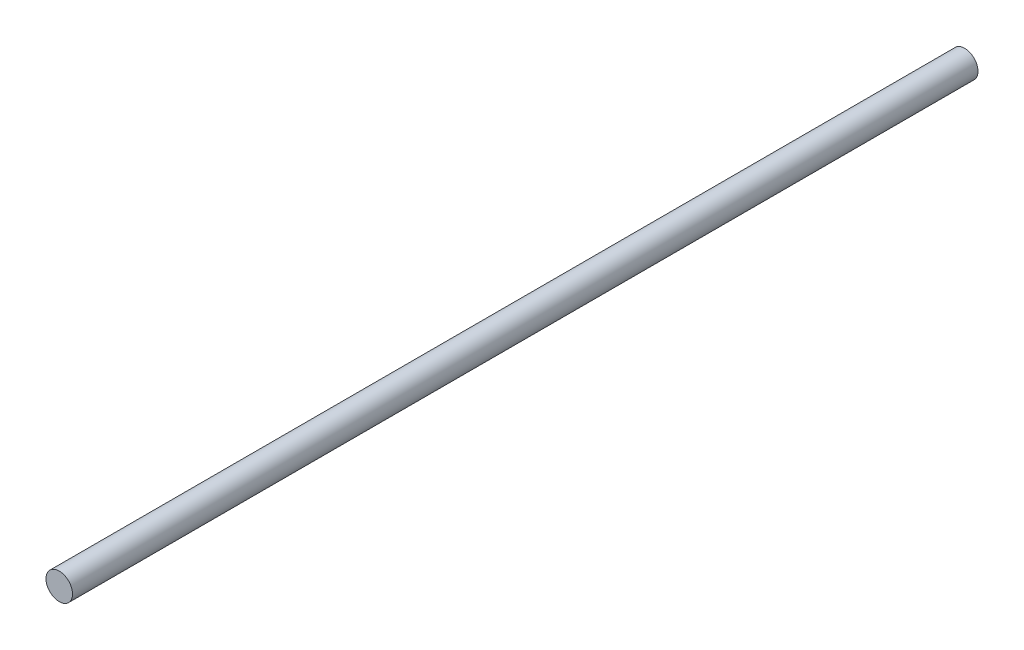
SolidWorks part; units mm, degrees
ref_plane "Płaszczyzna przednia" through (0, 0, 0) normal (0, 0, 1) x (1, 0, 0)
ref_plane "Płaszczyzna górna" through (0, 0, 0) normal (0, 1, 0) x (1, 0, 0)
ref_plane "Płaszczyzna prawa" through (0, 0, 0) normal (1, 0, 0) x (0, 0, -1)
sketch "Szkic1" plane through (0, 0, 0) normal (0, 0, 1) x (1, 0, 0)
  circle A0 centre (0, 0) radius 10
  dimension "D1" = 20
extrude "Dodanie-wyciągnięcie1" add sketch "Szkic1" along normal blind 682.34 contours A0
